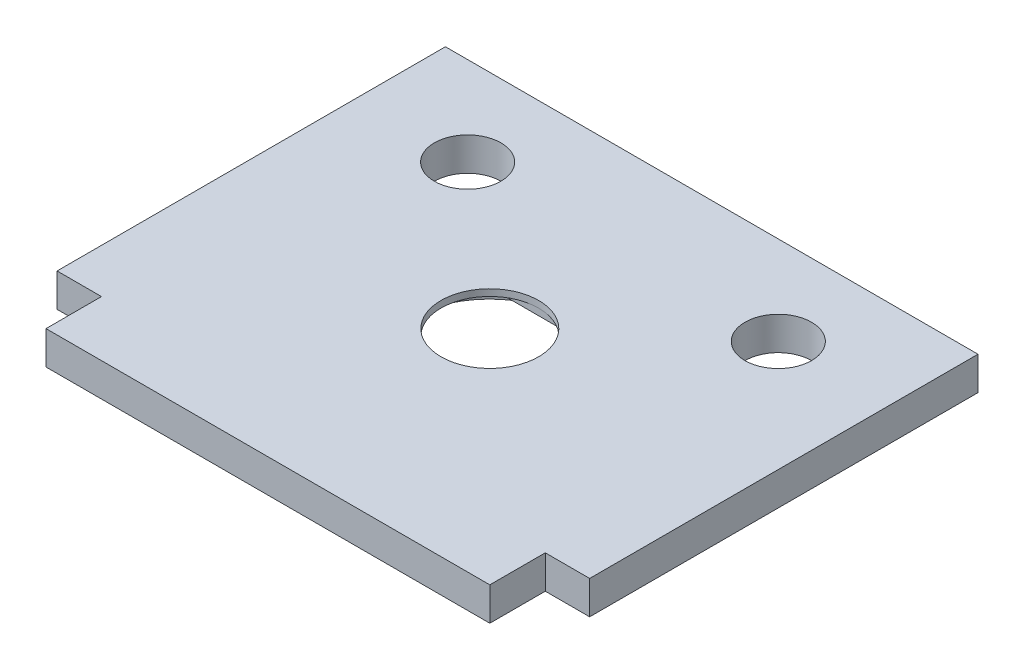
SolidWorks part; units mm, degrees
ref_plane "Front Plane" through (0, 0, 0) normal (0, 0, 1) x (1, 0, 0)
ref_plane "Top Plane" through (0, 0, 0) normal (0, 1, 0) x (1, 0, 0)
ref_plane "Right Plane" through (0, 0, 0) normal (1, 0, 0) x (0, 0, -1)
sketch "Sketch1" plane through (0, 0, 0) normal (0, 1, 0) x (1, 0, 0)
  line L0 (-13.4301, 17.5) -> (-13.4301, 0)
  line L1 (-13.4301, 0) -> (-11.4301, 0)
  line L2 (-11.4301, 0) -> (-11.4301, -2.5)
  line L3 (-11.4301, -2.5) -> (8.5699, -2.5)
  line L4 (8.5699, -2.5) -> (8.5699, 0)
  line L5 (8.5699, 0) -> (10.5699, 0)
  line L6 (10.5699, 0) -> (10.5699, 17.5)
  line L7 (10.5699, 17.5) -> (-13.4301, 17.5)
  dimension "D1" = 24
  dimension "D2" = 17.5
  dimension "D3" = 2.5
  dimension "D4" = 2
extrude "Boss-Extrude1" add sketch "Sketch1" along normal blind 1.5
sketch "Sketch3" plane through (0, 0, 0) normal (0, -1, 0) x (1, 0, 0)
  line L0 (-13.4301, -17.5) -> (-13.4301, 0) construction
  line L1 (-11.4301, 2.5) -> (8.5699, 2.5) construction
  circle A0 centre (-1.4301, -7.5) radius 3.75
  dimension "D1" = 7.5
  dimension "D2" = 12
  dimension "D3" = 10
extrude "Cut-Extrude1" cut sketch "Sketch3" against normal blind 0.9
sketch "Sketch4" plane through (0, 0.9, 0) normal (0, -1, 0) x (1, 0, 0)
  circle A0 centre (-1.4301, -7.5) radius 2.2
  dimension "D1" = 4.4
extrude "Cut-Extrude2" cut sketch "Sketch4" against normal blind 0.9
sketch "Sketch5" plane through (0, 0, 0) normal (0, -1, 0) x (1, 0, 0)
  line L2 (10.5699, 0) -> (10.5699, -17.5) construction
  line L3 (10.5699, -17.5) -> (-13.4301, -17.5) construction
  circle A0 centre (-8.4301, -13.5) radius 1.5
  circle A1 centre (5.5699, -13.5) radius 1.5
  dimension "D4" = 3
  dimension "D1" = 14
  dimension "D2" = 4
  dimension "D5" = 5
extrude "Cut-Extrude3" cut sketch "Sketch5" against normal blind 6
sketch "Sketch6" plane through (0, 0.9, 0) normal (0, -1, 0) x (1, 0, 0)
  line L0 (1.6068, -9.7) -> (-4.4669, -9.7)
  line L1 (1.6068, -5.3) -> (-4.4669, -5.3)
  line L3 (10.5699, -17.5) -> (-13.4301, -17.5) construction
  circle A0 centre (-1.4301, -7.5) radius 3.75 construction
  arc A1 (1.6068, -9.7) -> (1.6068, -5.3) centre (-1.4301, -7.5) ccw
  arc A2 (-4.4669, -5.3) -> (-4.4669, -9.7) centre (-1.4301, -7.5) ccw
  dimension "D1" = 4.4
extrude "Cut-Extrude4" cut sketch "Sketch6" against normal blind 0.3
